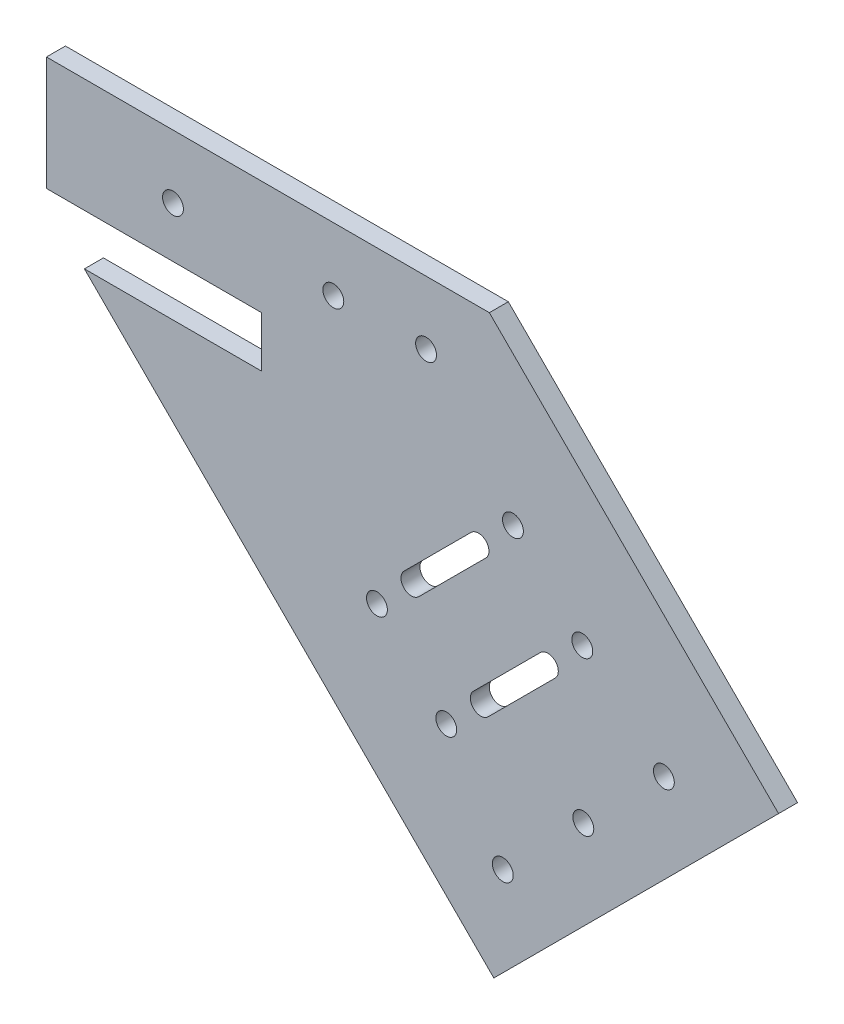
SolidWorks part; units mm, degrees
material "Thornel Mat VMA"
ref_plane "前视基准面" through (0, 0, 0) normal (0, 0, 1) x (1, 0, 0)
ref_plane "上视基准面" through (0, 0, 0) normal (0, 1, 0) x (1, 0, 0)
ref_plane "右视基准面" through (0, 0, 0) normal (1, 0, 0) x (0, 0, -1)
sketch "草图1" plane through (0, 0, 0) normal (0, 0, 1) x (1, 0, 0)
  line L0 (0, 0) -> (70, 0)
  line L1 (70, 0) -> (115.7107, -45.7107)
  line L2 (115.7107, -45.7107) -> (70.7107, -90.7107)
  line L3 (70.7107, -90.7107) -> (0, -20)
  line L6 (0, -20) -> (0, 0)
  dimension "D1" = 20
  dimension "D2" = 135
  dimension "D3" = 70
  dimension "D4" = 100
extrude "凸台-拉伸1" add sketch "草图1" along normal blind 3
sketch "草图2" plane through (0, 0, 3) normal (0, 0, 1) x (1, 0, 0)
  line L0 (63.6396, -83.6396) -> (108.6396, -38.6396) construction
  line L1 (0, -20) -> (70.7107, -90.7107) construction
  line L2 (115.7107, -45.7107) -> (70, 0) construction
  line L3 (0, -10) -> (80, -10) construction
  line L4 (0, 0) -> (0, -20) construction
  line L5 (57.6786, -43.2852) -> (68.2852, -32.6786) construction
  line L6 (56.5118, -42.1184) -> (67.1184, -31.5118)
  line L7 (70.7107, -90.7107) -> (115.7107, -45.7107) construction
  line L8 (90.9619, -20.9619) -> (45.9619, -65.9619) construction
  line L9 (85.4819, -15.4819) -> (40.4819, -60.4819) construction
  line L10 (51.442, -71.442) -> (96.442, -26.442) construction
  line L11 (58.8453, -44.4519) -> (69.4519, -33.8453)
  line L14 (62.9819, -37.9819) -> (73.942, -48.942) construction
  line L15 (68.6387, -54.2453) -> (79.2453, -43.6387) construction
  line L16 (69.8054, -55.412) -> (80.412, -44.8054)
  line L17 (67.472, -53.0786) -> (78.0786, -42.472)
  circle A0 centre (72.1249, -75.1543) radius 1.65
  circle A1 centre (80.6102, -66.669) radius 1.65 construction
  circle A2 centre (89.0955, -58.1838) radius 1.65 construction
  circle A3 centre (97.5807, -49.6985) radius 1.65
  circle A4 centre (20, -10) radius 1.65
  circle A5 centre (45.34, -10) radius 1.65
  circle A6 centre (60, -10) radius 1.65
  arc A9 (56.5118, -42.1184) -> (58.8453, -44.4519) centre (57.6786, -43.2852) ccw
  arc A10 (69.4519, -33.8453) -> (67.1184, -31.5118) centre (68.2852, -32.6786) ccw
  circle A11 centre (73.7299, -27.2338) radius 1.65
  circle A12 centre (52.2338, -48.7299) radius 1.65
  arc A13 (69.8054, -55.412) -> (67.472, -53.0786) centre (68.6387, -54.2453) cw
  arc A14 (78.0786, -42.472) -> (80.412, -44.8054) centre (79.2453, -43.6387) cw
  circle A15 centre (84.69, -38.194) radius 1.65
  circle A16 centre (63.194, -59.69) radius 1.65
  circle A17 centre (84.8528, -62.4264) radius 1.65
  point P34 (62.9819, -37.9819)
  point P47 (73.942, -48.942)
  dimension "D1" = 3.3
  dimension "D2" = 12
  dimension "D3" = 12
  dimension "D4" = 12
  dimension "D5" = 12
  dimension "D7" = 40
  dimension "D8" = 20
  dimension "D14" = 7.7
  dimension "D15" = 7.7
  dimension "D17" = 3.3
  dimension "D6" = 10
  dimension "D9" = 7.5
  dimension "D10" = 7.5
  dimension "D11" = 3.3
  dimension "D12" = 15.5
  dimension "D13" = 7.75
  dimension "D16" = 25
  dimension "D18" = 14.66
  dimension "D19" = 6
extrude "切除-拉伸1" cut sketch "草图2" against normal through all
sketch "草图3" plane through (0, 0, 0) normal (0, 0, -1) x (-1, 0, 0)
  line L0 (-34, -18) -> (2, -18)
  line L1 (0, -20) -> (-70.7107, -90.7107) construction
  line L2 (-34, -18) -> (-34, -26)
  line L3 (-34, -26) -> (-6, -26)
  line L4 (-6, -26) -> (2, -18)
  line L6 (-70, 0) -> (0, 0) construction
  dimension "D1" = 18
  dimension "D2" = 8
  dimension "D3" = 28
extrude "切除-拉伸2" cut sketch "草图3" against normal blind 10
